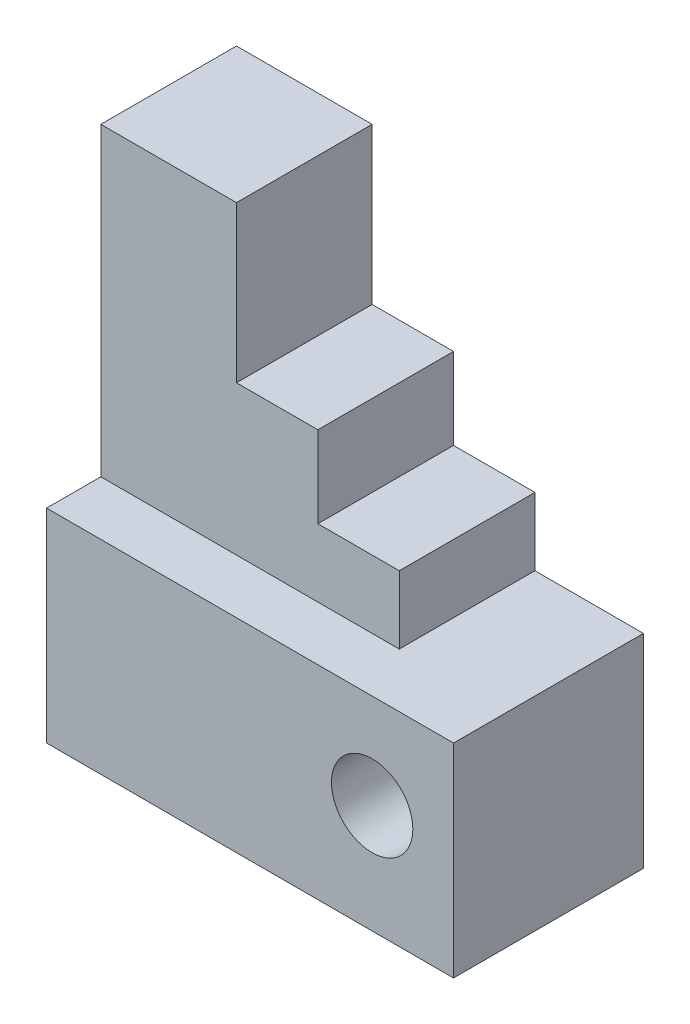
SolidWorks part; units mm, degrees
material "Aluminum Bronze"
ref_plane "Front Plane" through (0, 0, 0) normal (0, 0, 1) x (1, 0, 0)
ref_plane "Top Plane" through (0, 0, 0) normal (0, 1, 0) x (1, 0, 0)
ref_plane "Right Plane" through (0, 0, 0) normal (1, 0, 0) x (0, 0, -1)
sketch "Sketch1" plane through (0, 0, 0) normal (0, 0, 1) x (1, 0, 0)
  line L0 (-67.551, 0) -> (64.6967, 0) construction
  line L1 (12, -16) -> (-48, -16)
  line L7 (12, -16) -> (12, 14)
  line L8 (12, 14) -> (-48, 14)
  line L9 (-48, 14) -> (-48, -16)
  circle A0 centre (0, 0) radius 6
  dimension "D1" = 12
  dimension "D2" = 60
  dimension "D3" = 16
  dimension "D4" = 30
  dimension "D5" = 48
extrude "Boss-Extrude1" add sketch "Sketch1" along normal blind 28
sketch "Sketch4" plane through (0, 0, 0) normal (0, 0, -1) x (-1, 0, 0)
  line L0 (48, 14) -> (48, 59)
  line L1 (48, 59) -> (28, 59)
  line L2 (48, 14) -> (4, 14)
  line L3 (-12, 14) -> (48, 14) construction
  line L4 (4, 14) -> (4, 24)
  line L5 (4, 24) -> (16, 24)
  line L6 (16, 24) -> (16, 36)
  line L7 (16, 36) -> (28, 36)
  line L8 (28, 36) -> (28, 59)
  line L9 (48, -16) -> (-12, -16) construction
  dimension "D1" = 75
  dimension "D2" = 20
  dimension "D3" = 32
  dimension "D4" = 44
  dimension "D5" = 52
  dimension "D6" = 40
extrude "Boss-Extrude3" add sketch "Sketch4" against normal blind 20
